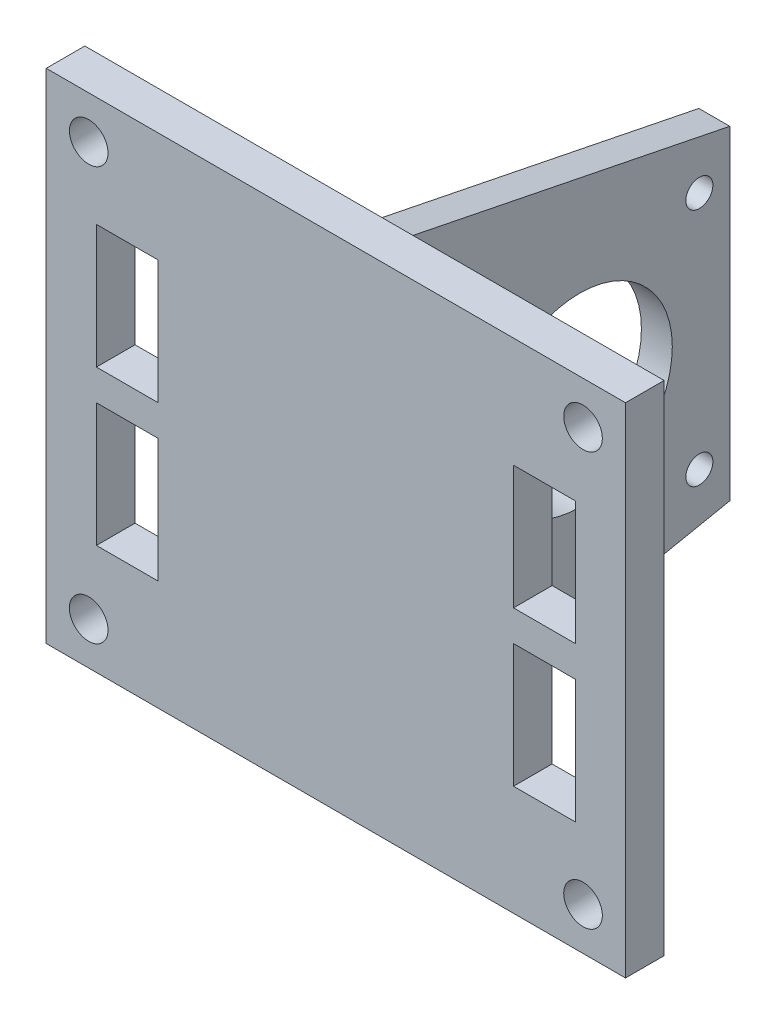
SolidWorks part; units mm, degrees
ref_plane "前基準面" through (0, 0, 0) normal (0, 0, 1) x (1, 0, 0)
ref_plane "上基準面" through (0, 0, 0) normal (0, 1, 0) x (1, 0, 0)
ref_plane "右基準面" through (0, 0, 0) normal (1, 0, 0) x (0, 0, -1)
sketch "草圖1" plane through (0, 0, 0) normal (0, 0, 1) x (1, 0, 0)
  line L1 (37.5, -32.25) -> (-37.5, -32.25)
  line L2 (37.5, -32.25) -> (37.5, 32.25)
  line L3 (37.5, 32.25) -> (-37.5, 32.25)
  line L4 (-37.5, -32.25) -> (-37.5, 32.25)
  line L5 (0, 32.25) -> (0, -32.25) construction
  line L6 (37.5, 0) -> (-37.5, 0) construction
  point P0 (0, 0)
  dimension "D1" = 75
  dimension "D2" = 64.5
extrude "填料-伸長1" add sketch "草圖1" along normal blind 5
sketch "草圖2" plane through (0, 0, 0) normal (1, 0, 0) x (0, 0, -1)
  line L0 (0, 29.8702) -> (0, 0)
  line L4 (44, 21) -> (44, -21)
  line L5 (44, 21) -> (0, 29.8702)
  line L6 (0, 0) -> (0, -29.8702)
  line L7 (33.1041, 0) -> (1.1057, 0) construction
  line L8 (44, -21) -> (0, -29.8702)
  dimension "D1" = 44
extrude "填料-伸長2" add sketch "草圖2" along normal blind 2 and the other way blind 2
sketch "草圖3" plane through (2, 0, 0) normal (1, 0, 0) x (0, 0, -1)
  line L0 (44, 0) -> (0, 0) construction
  line L1 (44, -21) -> (44, 21) construction
  line L2 (24.5596, 0) -> (24.5596, 28.5233) construction
  line L3 (24.5596, 0) -> (35.9335, 11.3739) construction
  circle A1 centre (24.5596, 0) radius 12
  circle A2 centre (9.0596, 15.5) radius 1.75
  circle A6 centre (24.5596, 0) radius 21.9203
  circle A7 centre (40.0596, 15.5) radius 1.75
  circle A8 centre (40.0596, -15.5) radius 1.75
  circle A9 centre (9.0596, -15.5) radius 1.75
  dimension "D1" = 15.5
  dimension "D2" = 24
  dimension "D4" = 3.5
  dimension "D3" = 45
  dimension "D5" = 15.5
sketch "草圖4" plane through (0, 0, 0) normal (0, 0, -1) x (-1, 0, 0)
  line L0 (-37.5, 32.25) -> (37.5, 32.25) construction
  line L1 (37.5, 32.25) -> (37.5, -32.25) construction
  line L2 (0, 32.25) -> (0, -5.7529) construction
  line L3 (-37.5, 0) -> (4.9081, 0) construction
  line L4 (-37.5, -32.25) -> (-37.5, 32.25) construction
  circle A0 centre (32, 26.75) radius 2.5
  circle A1 centre (32, -26.75) radius 2.5
  circle A2 centre (-32, -26.75) radius 2.5
  circle A3 centre (-32, 26.75) radius 2.5
  dimension "D1" = 5
  dimension "D2" = 5.5
  dimension "D3" = 5.5
extrude "除料-伸長1" cut sketch "草圖3" against normal through all contours A7 A6 | A7 A6 | A1 | A2 | A8 | A9
extrude "除料-伸長2" cut sketch "草圖4" against normal through all contours A3 | A0 | A1 | A2
sketch "草圖5" plane through (0, 0, 0) normal (0, 0, -1) x (-1, 0, 0)
  line L0 (-37.5, 0) -> (-8.5156, 0) construction
  line L1 (-37.5, -32.25) -> (-37.5, 32.25) construction
  line L2 (0, 32.25) -> (0, 0) construction
  line L3 (-37.5, 32.25) -> (37.5, 32.25) construction
  line L4 (-23, 10) -> (-37.5, 10) construction
  line L5 (-31, 2) -> (-23, 2)
  line L6 (-31, 2) -> (-31, 18)
  line L7 (-31, 18) -> (-23, 18)
  line L8 (-23, 2) -> (-23, 18)
  line L9 (-31, -18) -> (-23, -18)
  line L10 (-23, -2) -> (-23, -18)
  line L11 (-31, -2) -> (-23, -2)
  line L12 (-31, -2) -> (-31, -18)
  line L13 (31, -2) -> (31, -18)
  line L14 (31, -2) -> (23, -2)
  line L15 (23, -2) -> (23, -18)
  line L16 (31, -18) -> (23, -18)
  line L17 (31, 18) -> (23, 18)
  line L18 (23, 2) -> (23, 18)
  line L19 (31, 2) -> (23, 2)
  line L20 (31, 2) -> (31, 18)
  dimension "D1" = 6.5
  dimension "D2" = 8
  dimension "D3" = 16
  dimension "D4" = 10
extrude "除料-伸長3" cut sketch "草圖5" against normal through all
